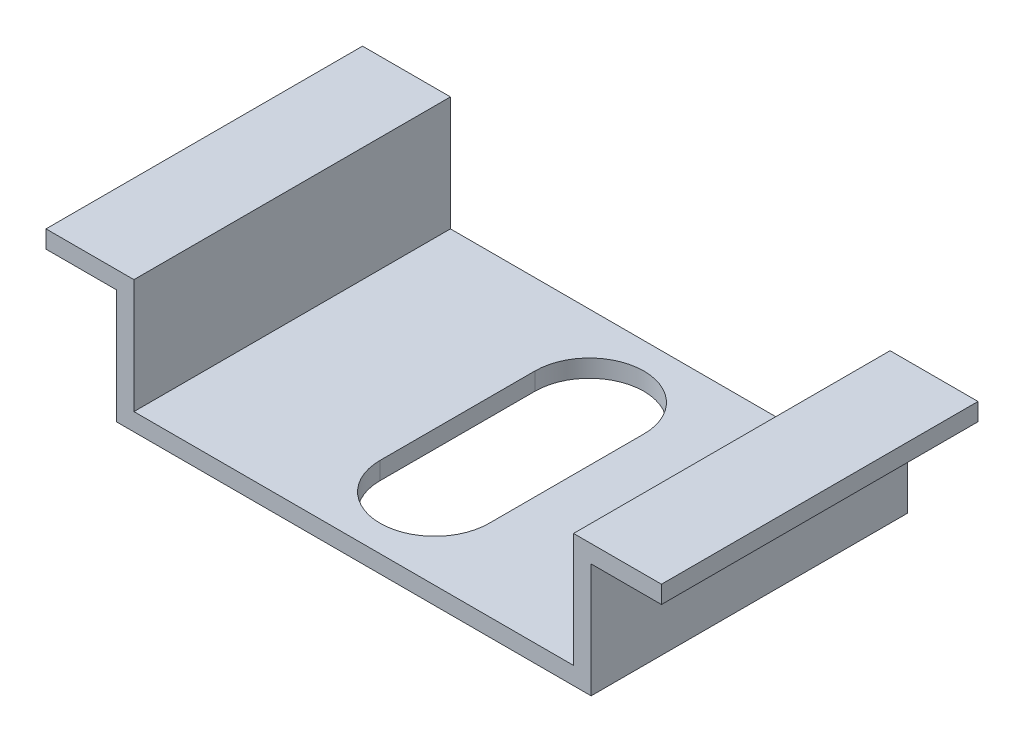
SolidWorks part; units mm, degrees
ref_plane "Front Plane" through (0, 0, 0) normal (0, 0, 1) x (1, 0, 0)
ref_plane "Top Plane" through (0, 0, 0) normal (0, 1, 0) x (1, 0, 0)
ref_plane "Right Plane" through (0, 0, 0) normal (1, 0, 0) x (0, 0, -1)
sketch "Sketch1" plane through (0, 0, 0) normal (0, 1, 0) x (1, 0, 0)
  line L0 (0, 0) -> (-35, 0)
  line L1 (-35, 0) -> (-35, -175)
  line L2 (-35, -175) -> (0, -175)
  line L3 (0, -175) -> (0, 0)
extrude "Boss-Extrude1" add sketch "Sketch1" against normal blind 7.5
sketch "Sketch2" plane through (0, 0, 0) normal (0, 0, -1) x (-1, 0, 0)
  line L0 (30, 0) -> (5, 0)
  line L1 (5, 0) -> (5, -6.5)
  line L2 (5, -6.5) -> (30, -6.5)
  line L3 (30, -6.5) -> (30, 0)
extrude "Cut-Extrude1" cut sketch "Sketch2" against normal through all
sketch "Sketch3" plane through (0, -7.5, 0) normal (0, -1, 0) x (1, 0, 0)
  line L0 (-20.6, 0) -> (-14.4, 0)
  line L1 (-14.4, 0) -> (-14.4, 3.4)
  line L2 (-20.6, 3.4) -> (-20.6, 0)
  arc A0 (-14.4, 3.4) -> (-20.6, 3.4) centre (-17.5, 3.4) ccw
extrude "Cut-Extrude2" cut sketch "Sketch3" against normal through all
sketch "Sketch4" plane through (0, 0, 0) normal (0, 0, -1) x (-1, 0, 0)
  line L0 (35, -1) -> (31, -1)
  line L1 (31, -1) -> (31, -7.5)
  line L2 (31, -7.5) -> (35, -7.5)
  line L3 (35, -7.5) -> (35, -1)
extrude "Cut-Extrude3" cut sketch "Sketch4" against normal through all
sketch "Sketch5" plane through (0, 0, 0) normal (0, 0, -1) x (-1, 0, 0)
  line L0 (4, -1) -> (0, -1)
  line L1 (0, -1) -> (0, -7.5)
  line L2 (0, -7.5) -> (4, -7.5)
  line L3 (4, -7.5) -> (4, -1)
extrude "Cut-Extrude4" cut sketch "Sketch5" against normal through all
sketch "Sketch6" plane through (0, -7.5, 0) normal (0, -1, 0) x (1, 0, 0)
  line L0 (-14.4, 175) -> (-20.6, 175)
  line L1 (-20.6, 175) -> (-20.6, 169.6)
  line L2 (-14.4, 169.6) -> (-14.4, 175)
  arc A0 (-20.6, 169.6) -> (-14.4, 169.6) centre (-17.5, 169.6) ccw
extrude "Cut-Extrude5" cut sketch "Sketch6" against normal through all
sketch "Sketch7" plane through (0, -6.5, 0) normal (0, 1, 0) x (-1, 0, 0)
  line L0 (14.4, 103.4) -> (14.4, 94.6)
  line L1 (20.6, 94.6) -> (20.6, 103.4)
  arc A0 (14.4, 94.6) -> (20.6, 94.6) centre (17.5, 94.6) ccw
  arc A1 (20.6, 103.4) -> (14.4, 103.4) centre (17.5, 103.4) ccw
extrude "Cut-Extrude6" cut sketch "Sketch7" against normal through all
sketch "Sketch8" plane through (0, -6.5, 0) normal (0, 1, 0) x (-1, 0, 0)
  line L0 (14.4, 78.4) -> (14.4, 69.6)
  line L1 (20.6, 69.6) -> (20.6, 78.4)
  arc A0 (14.4, 69.6) -> (20.6, 69.6) centre (17.5, 69.6) ccw
  arc A1 (20.6, 78.4) -> (14.4, 78.4) centre (17.5, 78.4) ccw
extrude "Cut-Extrude7" cut sketch "Sketch8" against normal through all
sketch "Sketch9" plane through (0, -6.5, 0) normal (0, 1, 0) x (-1, 0, 0)
  line L0 (14.4, 28.4) -> (14.4, 19.6)
  line L1 (20.6, 19.6) -> (20.6, 28.4)
  arc A0 (20.6, 28.4) -> (14.4, 28.4) centre (17.5, 28.4) ccw
  arc A1 (14.4, 19.6) -> (20.6, 19.6) centre (17.5, 19.6) ccw
extrude "Cut-Extrude8" cut sketch "Sketch9" against normal through all
sketch "Sketch10" plane through (0, -6.5, 0) normal (0, 1, 0) x (-1, 0, 0)
  line L0 (14.4, 153.4) -> (14.4, 144.6)
  line L1 (20.6, 144.6) -> (20.6, 153.4)
  arc A0 (14.4, 144.6) -> (20.6, 144.6) centre (17.5, 144.6) ccw
  arc A1 (20.6, 153.4) -> (14.4, 153.4) centre (17.5, 153.4) ccw
extrude "Cut-Extrude9" cut sketch "Sketch10" against normal through all
sketch "Sketch11" plane through (0, -6.5, 0) normal (0, 1, 0) x (-1, 0, 0)
  line L0 (14.4, 128.4) -> (14.4, 119.6)
  line L1 (20.6, 119.6) -> (20.6, 128.4)
  arc A0 (14.4, 119.6) -> (20.6, 119.6) centre (17.5, 119.6) ccw
  arc A1 (20.6, 128.4) -> (14.4, 128.4) centre (17.5, 128.4) ccw
extrude "Cut-Extrude10" cut sketch "Sketch11" against normal through all
sketch "Sketch12" plane through (0, -7.5, 0) normal (0, -1, 0) x (1, 0, 0)
  line L0 (-20.6, 53.4) -> (-20.6, 44.6)
  line L1 (-14.4, 44.6) -> (-14.4, 53.4)
  arc A0 (-20.6, 44.6) -> (-14.4, 44.6) centre (-17.5, 44.6) ccw
  arc A1 (-14.4, 53.4) -> (-20.6, 53.4) centre (-17.5, 53.4) ccw
extrude "Cut-Extrude11" cut sketch "Sketch12" against normal through all
sketch "Sketch13" plane through (0, 0, 0) normal (0, 0, -1) x (-1, 0, 0)
  line L0 (39.5416, 10.9748) -> (39.5416, -19.8623)
  line L1 (39.5416, 10.9748) -> (-14.5311, 10.9748)
  line L2 (39.5416, -19.8623) -> (-14.5311, -19.8623)
  line L3 (-14.5311, 10.9748) -> (-14.5311, -19.8623)
extrude "Cut-Extrude12" cut sketch "Sketch13" against normal blind 15
sketch "Sketch14" plane through (0, 0, 175) normal (0, 0, 1) x (1, 0, 0)
  line L0 (-40.3882, -12.4239) -> (-40.3882, 14.6296)
  line L1 (-40.3882, -12.4239) -> (8.6142, -12.4239)
  line L2 (-40.3882, 14.6296) -> (8.6142, 14.6296)
  line L3 (8.6142, -12.4239) -> (8.6142, 14.6296)
extrude "Cut-Extrude13" cut sketch "Sketch14" against normal blind 142
